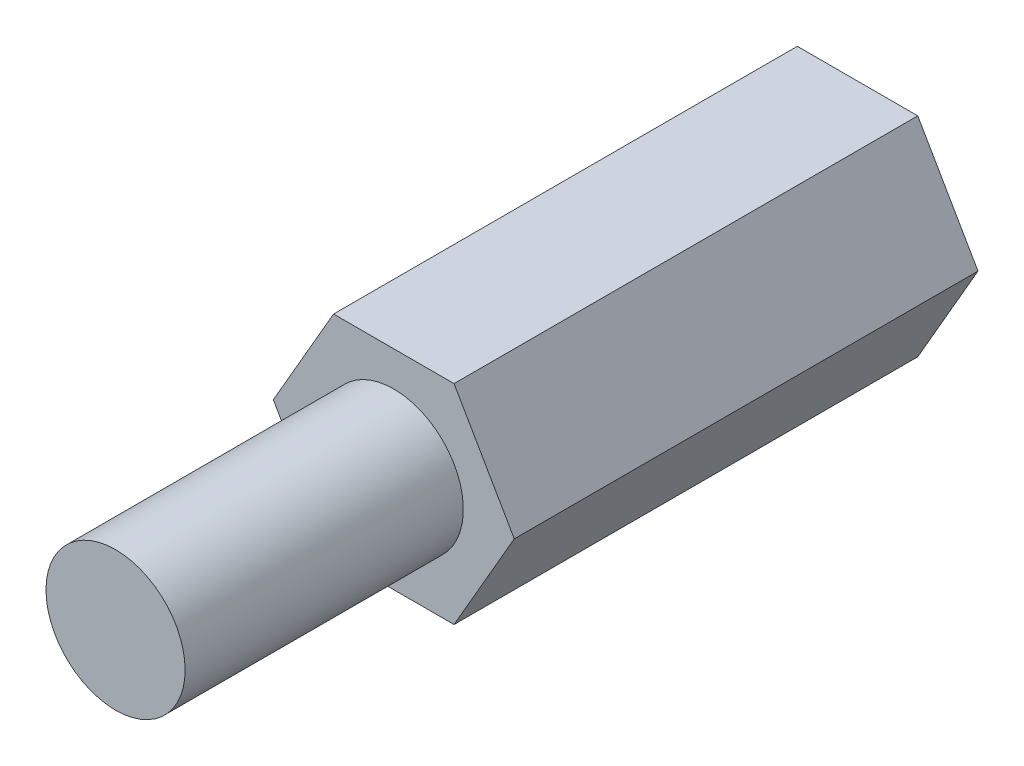
SolidWorks part; units mm, degrees
material "Aluminum"
ref_plane "Front Plane" through (0, 0, 0) normal (0, 0, 1) x (1, 0, 0)
ref_plane "Top Plane" through (0, 0, 0) normal (0, 1, 0) x (1, 0, 0)
ref_plane "Right Plane" through (0, 0, 0) normal (1, 0, 0) x (0, 0, -1)
sketch "Sketch1" plane through (0, 0, 0) normal (0, 0, 1) x (1, 0, 0)
  circle A0 centre (0, 0) radius 1.5
  dimension "D1" = 3
extrude "Boss-Extrude1" add sketch "Sketch1" along normal blind 6
sketch "Sketch2" plane through (0, 0, 0) normal (0, 0, -1) x (-1, 0, 0)
  line L1 (1.299, 2.25) -> (-1.299, 2.25)
  line L2 (-1.299, 2.25) -> (-2.5981, 0)
  line L3 (-2.5981, 0) -> (-1.299, -2.25)
  line L4 (-1.299, -2.25) -> (1.299, -2.25)
  line L5 (1.299, -2.25) -> (2.5981, 0)
  line L6 (2.5981, 0) -> (1.299, 2.25)
  circle A1 centre (0, 0) radius 2.25 construction
  dimension "D1" = 4.5
extrude "Boss-Extrude2" add sketch "Sketch2" along normal blind 10
sketch "Sketch3" plane through (0, 0, -10) normal (0, 0, -1) x (-1, 0, 0)
  circle A0 centre (0, 0) radius 1.5
  dimension "D1" = 3
extrude "Cut-Extrude1" cut sketch "Sketch3" against normal blind 6
